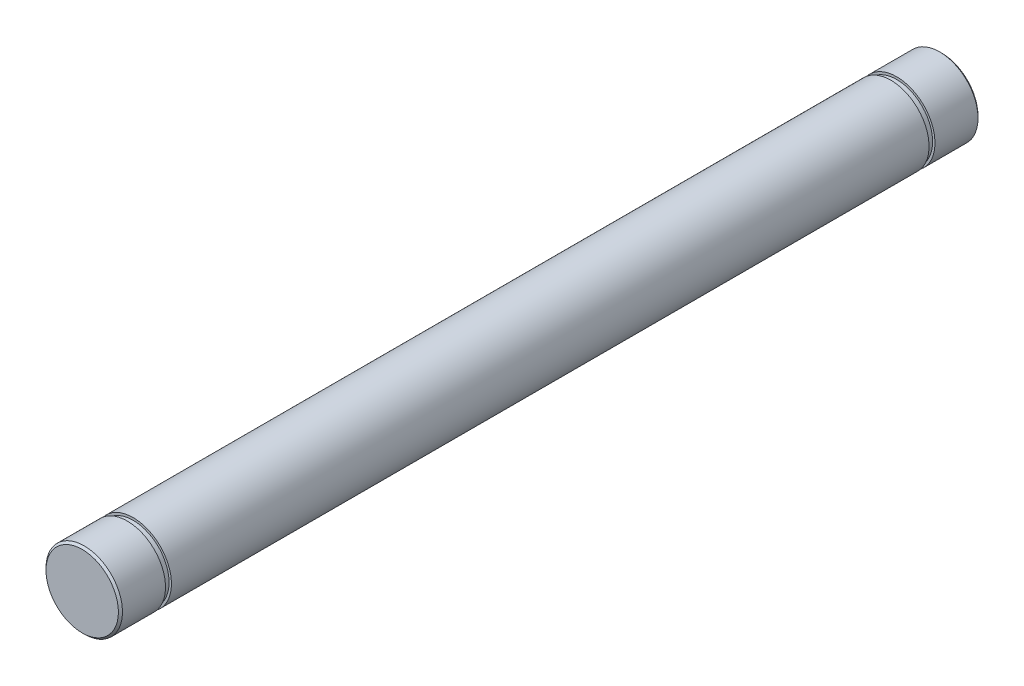
SolidWorks part; units mm, degrees
material "AISI 1045 Steel, cold drawn"
ref_plane "Front Plane" through (0, 0, 0) normal (0, 0, 1) x (1, 0, 0)
ref_plane "Top Plane" through (0, 0, 0) normal (0, 1, 0) x (1, 0, 0)
ref_plane "Right Plane" through (0, 0, 0) normal (1, 0, 0) x (0, 0, -1)
sketch "Sketch1" plane through (0, 0, 0) normal (0, 0, 1) x (1, 0, 0)
  circle A0 centre (0, 0) radius 4.7625
  dimension "D1" = 9.525
extrude "Boss-Extrude1" add sketch "Sketch1" along normal blind 107.061
ref_plane "Plane1" through (0, 0, 100.711) normal (0, 0, 1) x (1, 0, 0)
sketch "Sketch2" plane through (0, 0, 100.711) normal (0, 0, 1) x (1, 0, 0)
  circle A0 centre (0, 0) radius 4.4704
  circle A1 centre (0, 0) radius 5.5149
  dimension "D1" = 8.9408
extrude "Cut-Extrude1" cut sketch "Sketch2" along normal blind 0.7366
ref_plane "Plane2" through (0, 0, 6.35) normal (0, 0, -1) x (-1, 0, 0)
sketch "Sketch3" plane through (0, 0, 6.35) normal (0, 0, -1) x (-1, 0, 0)
  circle A0 centre (0, 0) radius 4.4704
  circle A1 centre (0, 0) radius 6.35
  dimension "D1" = 12.7
  dimension "D2" = 8.9408
extrude "Cut-Extrude2" cut sketch "Sketch3" along normal blind 0.7366
chamfer "Chamfer1" distance 0.254 angle 45 2 edges at (4.7625, 0, 107.061) (4.7625, 0, 0)
